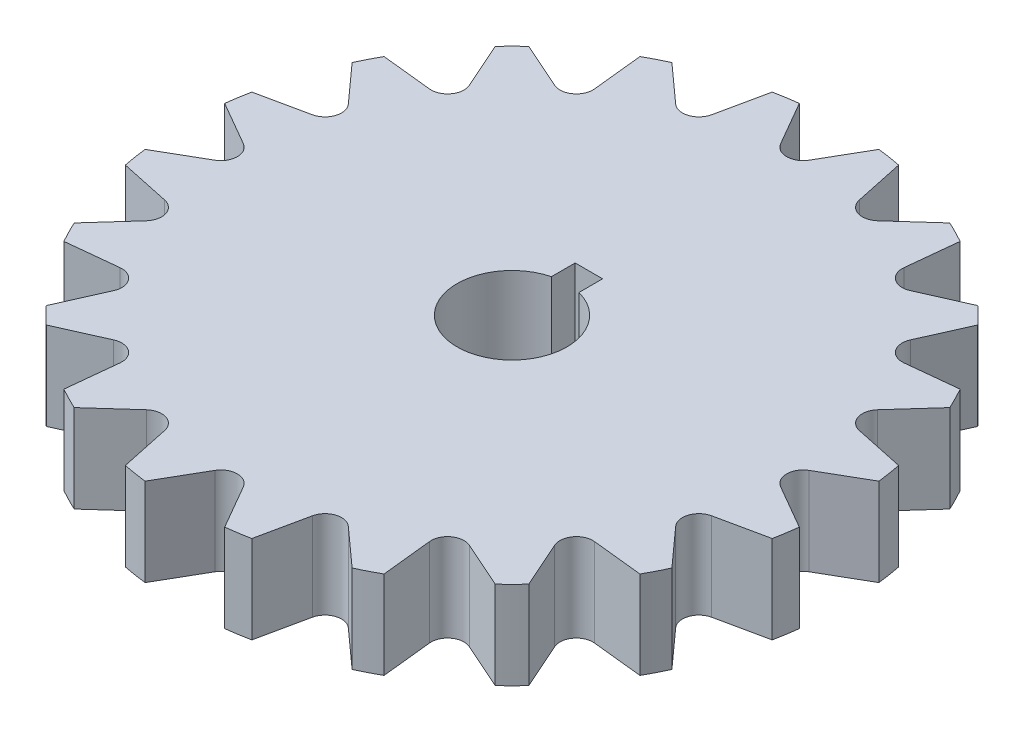
SolidWorks part; units mm, degrees
ref_plane "Front Plane" through (0, 0, 0) normal (0, 0, 1) x (1, 0, 0)
ref_plane "Top Plane" through (0, 0, 0) normal (0, 1, 0) x (1, 0, 0)
ref_plane "Right Plane" through (0, 0, 0) normal (1, 0, 0) x (0, 0, -1)
sketch "Sketch1" plane through (0, 0, 0) normal (0, 1, 0) x (1, 0, 0)
  line L0 (0, 0) -> (0, 30) construction
  line L1 (3.75, 30) -> (-3.75, 30)
  line L2 (-3.75, 30) -> (-1.299, 25.7548)
  line L3 (1.299, 25.7548) -> (3.75, 30)
  line L4 (9.1941, 24.0929) -> (12.837, 27.3729)
  line L5 (5.704, 29.6905) -> (6.7232, 24.8957)
  line L6 (12.837, 27.3729) -> (5.704, 29.6905)
  line L7 (16.1892, 20.0725) -> (20.6674, 22.0663)
  line L8 (14.5997, 26.4747) -> (14.0874, 21.5996)
  line L9 (20.6674, 22.0663) -> (14.5997, 26.4747)
  line L10 (21.5996, 14.0874) -> (26.4747, 14.5997)
  line L11 (22.0663, 20.6674) -> (20.0725, 16.1892)
  line L12 (26.4747, 14.5997) -> (22.0663, 20.6674)
  line L13 (24.8957, 6.7232) -> (29.6905, 5.704)
  line L14 (27.3729, 12.837) -> (24.0929, 9.1941)
  line L15 (29.6905, 5.704) -> (27.3729, 12.837)
  line L16 (25.7548, -1.299) -> (30, -3.75)
  line L17 (30, 3.75) -> (25.7548, 1.299)
  line L18 (30, -3.75) -> (30, 3.75)
  line L19 (24.0929, -9.1941) -> (27.3729, -12.837)
  line L20 (29.6905, -5.704) -> (24.8957, -6.7232)
  line L21 (27.3729, -12.837) -> (29.6905, -5.704)
  line L22 (20.0725, -16.1892) -> (22.0663, -20.6674)
  line L23 (26.4747, -14.5997) -> (21.5996, -14.0874)
  line L24 (22.0663, -20.6674) -> (26.4747, -14.5997)
  line L25 (14.0874, -21.5996) -> (14.5997, -26.4747)
  line L26 (20.6674, -22.0663) -> (16.1892, -20.0725)
  line L27 (14.5997, -26.4747) -> (20.6674, -22.0663)
  line L28 (6.7232, -24.8957) -> (5.704, -29.6905)
  line L29 (12.837, -27.3729) -> (9.1941, -24.0929)
  line L30 (5.704, -29.6905) -> (12.837, -27.3729)
  line L31 (-1.299, -25.7548) -> (-3.75, -30)
  line L32 (3.75, -30) -> (1.299, -25.7548)
  line L33 (-3.75, -30) -> (3.75, -30)
  line L34 (-9.1941, -24.0929) -> (-12.837, -27.3729)
  line L35 (-5.704, -29.6905) -> (-6.7232, -24.8957)
  line L36 (-12.837, -27.3729) -> (-5.704, -29.6905)
  line L37 (-16.1892, -20.0725) -> (-20.6674, -22.0663)
  line L38 (-14.5997, -26.4747) -> (-14.0874, -21.5996)
  line L39 (-20.6674, -22.0663) -> (-14.5997, -26.4747)
  line L40 (-21.5996, -14.0874) -> (-26.4747, -14.5997)
  line L41 (-22.0663, -20.6674) -> (-20.0725, -16.1892)
  line L42 (-26.4747, -14.5997) -> (-22.0663, -20.6674)
  line L43 (-24.8957, -6.7232) -> (-29.6905, -5.704)
  line L44 (-27.3729, -12.837) -> (-24.0929, -9.1941)
  line L45 (-29.6905, -5.704) -> (-27.3729, -12.837)
  line L46 (-25.7548, 1.299) -> (-30, 3.75)
  line L47 (-30, -3.75) -> (-25.7548, -1.299)
  line L48 (-30, 3.75) -> (-30, -3.75)
  line L49 (-24.0929, 9.1941) -> (-27.3729, 12.837)
  line L50 (-29.6905, 5.704) -> (-24.8957, 6.7232)
  line L51 (-27.3729, 12.837) -> (-29.6905, 5.704)
  line L52 (-20.0725, 16.1892) -> (-22.0663, 20.6674)
  line L53 (-26.4747, 14.5997) -> (-21.5996, 14.0874)
  line L54 (-22.0663, 20.6674) -> (-26.4747, 14.5997)
  line L55 (-14.0874, 21.5996) -> (-14.5997, 26.4747)
  line L56 (-20.6674, 22.0663) -> (-16.1892, 20.0725)
  line L57 (-14.5997, 26.4747) -> (-20.6674, 22.0663)
  line L58 (-6.7232, 24.8957) -> (-5.704, 29.6905)
  line L59 (-12.837, 27.3729) -> (-9.1941, 24.0929)
  line L60 (-5.704, 29.6905) -> (-12.837, 27.3729)
  line L61 (0, 0) -> (1.299, 25.7548) construction
  line L62 (0, 0) -> (9.1941, 24.0929) construction
  line L64 (-1.25, 0) -> (1.25, 0)
  line L65 (-1.25, 0) -> (-1.25, 7)
  line L66 (-1.25, 7) -> (1.25, 7)
  line L67 (1.25, 0) -> (1.25, 7)
  circle A0 centre (0, 0) radius 5
  circle A1 centre (0, 0) radius 30
  arc A2 (-1.299, 25.7548) -> (1.299, 25.7548) centre (0, 26.5048) ccw
  arc A3 (6.7232, 24.8957) -> (9.1941, 24.0929) centre (8.1904, 25.2076) ccw
  circle A4 centre (0, 0) radius 5
  arc A5 (14.0874, 21.5996) -> (16.1892, 20.0725) centre (15.5791, 21.4428) ccw
  circle A6 centre (0, 0) radius 5
  arc A7 (20.0725, 16.1892) -> (21.5996, 14.0874) centre (21.4428, 15.5791) ccw
  circle A8 centre (0, 0) radius 5
  arc A9 (24.0929, 9.1941) -> (24.8957, 6.7232) centre (25.2076, 8.1904) ccw
  circle A10 centre (0, 0) radius 5
  arc A11 (25.7548, 1.299) -> (25.7548, -1.299) centre (26.5048, 0) ccw
  circle A12 centre (0, 0) radius 5
  arc A13 (24.8957, -6.7232) -> (24.0929, -9.1941) centre (25.2076, -8.1904) ccw
  circle A14 centre (0, 0) radius 5
  arc A15 (21.5996, -14.0874) -> (20.0725, -16.1892) centre (21.4428, -15.5791) ccw
  circle A16 centre (0, 0) radius 5
  arc A17 (16.1892, -20.0725) -> (14.0874, -21.5996) centre (15.5791, -21.4428) ccw
  circle A18 centre (0, 0) radius 5
  arc A19 (9.1941, -24.0929) -> (6.7232, -24.8957) centre (8.1904, -25.2076) ccw
  circle A20 centre (0, 0) radius 5
  arc A21 (1.299, -25.7548) -> (-1.299, -25.7548) centre (0, -26.5048) ccw
  circle A22 centre (0, 0) radius 5
  arc A23 (-6.7232, -24.8957) -> (-9.1941, -24.0929) centre (-8.1904, -25.2076) ccw
  circle A24 centre (0, 0) radius 5
  arc A25 (-14.0874, -21.5996) -> (-16.1892, -20.0725) centre (-15.5791, -21.4428) ccw
  circle A26 centre (0, 0) radius 5
  arc A27 (-20.0725, -16.1892) -> (-21.5996, -14.0874) centre (-21.4428, -15.5791) ccw
  circle A28 centre (0, 0) radius 5
  arc A29 (-24.0929, -9.1941) -> (-24.8957, -6.7232) centre (-25.2076, -8.1904) ccw
  circle A30 centre (0, 0) radius 5
  arc A31 (-25.7548, -1.299) -> (-25.7548, 1.299) centre (-26.5048, 0) ccw
  circle A32 centre (0, 0) radius 5
  arc A33 (-24.8957, 6.7232) -> (-24.0929, 9.1941) centre (-25.2076, 8.1904) ccw
  circle A34 centre (0, 0) radius 5
  arc A35 (-21.5996, 14.0874) -> (-20.0725, 16.1892) centre (-21.4428, 15.5791) ccw
  circle A36 centre (0, 0) radius 5
  arc A37 (-16.1892, 20.0725) -> (-14.0874, 21.5996) centre (-15.5791, 21.4428) ccw
  circle A38 centre (0, 0) radius 5
  arc A39 (-9.1941, 24.0929) -> (-6.7232, 24.8957) centre (-8.1904, 25.2076) ccw
  circle A40 centre (0, 0) radius 5
  point P8 (0, 30)
  point P11 (0, 23.5048)
  dimension "D1" = 10
  dimension "D2" = 60
  dimension "D5" = 1.5
  dimension "D3" = 7.5
  dimension "D4" = 60
  dimension "D7" = 18
  dimension "D8" = 7
  dimension "D9" = 2.5
  dimension "D10" = 1.25
  dimension "D6" = 20
extrude "Boss-Extrude1" add sketch "Sketch1" along normal blind 8 contours A39 L59 A1 L55 A37 L56 L52 A35 L53 L49 A33 L50 L46 A31 L47 L43 A29 L44 L40 A27 L41 L37 A25 L38 L34 A23 L35 L31 A21 L32 L28 A19 L29 L25 A17 L26 L22 A15 L23
